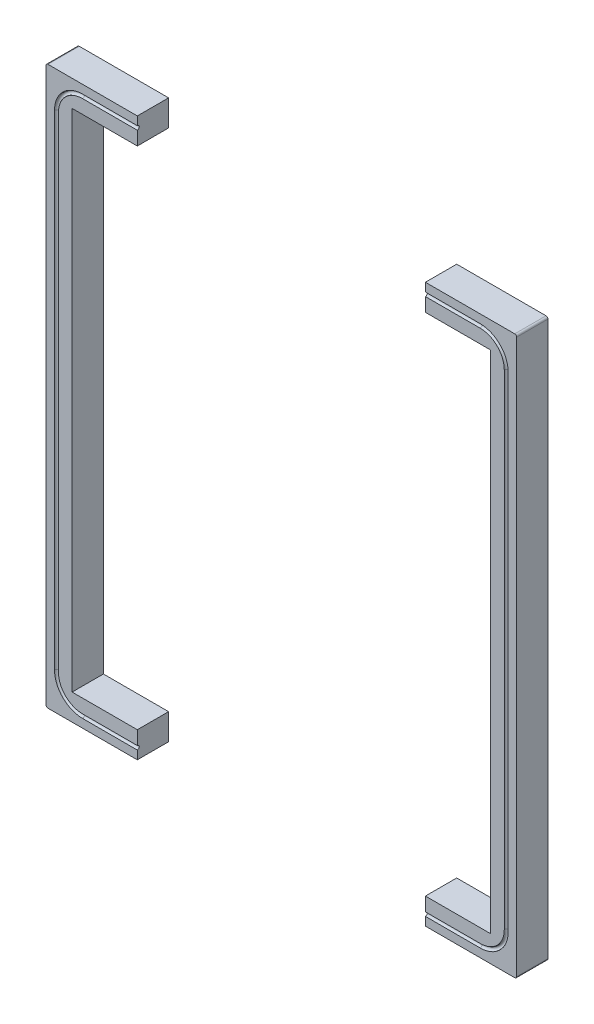
SolidWorks part; units mm, degrees
material "Melamine resin"
ref_plane "Plano frontal" through (0, 0, 0) normal (0, 0, 1) x (1, 0, 0)
ref_plane "Plano superior" through (0, 0, 0) normal (0, 1, 0) x (1, 0, 0)
ref_plane "Plano direito" through (0, 0, 0) normal (1, 0, 0) x (0, 0, -1)
sketch "Esboço1" plane through (0, 0, 0) normal (0, 0, 1) x (1, 0, 0)
  line L1 (-76.152, 222.0831) -> (104.318, 222.0831)
  line L2 (-76.152, 222.0831) -> (-76.152, 8.2431)
  line L3 (-76.152, 8.2431) -> (104.318, 8.2431)
  line L4 (104.318, 222.0831) -> (104.318, 8.2431)
  dimension "D1" = 180.47
  dimension "D2" = 213.84
extrude "Ressalto-extrusão1" add sketch "Esboço1" along normal blind 12
fillet "Filete2" radius 0.7366 1 edges at (104.318, 222.0831, 6)
fillet "Filete3" radius 0.7366 1 edges at (104.318, 8.2431, 6)
fillet "Filete4" radius 0.7366 1 edges at (-76.152, 8.2431, 6)
fillet "Filete5" radius 0.7366 1 edges at (-76.152, 222.0831, 6)
sketch "Esboço2" plane through (0, 0, 12) normal (0, 0, 1) x (1, 0, 0)
  line L0 (69.318, 222.0831) -> (103.5846, 222.0831) construction
  line L1 (-66.152, 212.0831) -> (94.318, 212.0831)
  line L2 (-66.152, 212.0831) -> (-66.152, 18.2431)
  line L3 (-66.152, 18.2431) -> (94.318, 18.2431)
  line L4 (94.318, 212.0831) -> (94.318, 18.2431)
  line L5 (104.318, 8.9797) -> (104.318, 221.3465) construction
  line L6 (-75.4154, 8.2431) -> (103.5814, 8.2431) construction
  line L7 (-76.152, 221.3465) -> (-76.152, 8.9797) construction
  dimension "D1" = 10
  dimension "D2" = 10
  dimension "D3" = 10
  dimension "D4" = 10
extrude "Corte-extrusão1" cut sketch "Esboço2" against normal up to next
sketch "Esboço3" plane through (0, 0, 12) normal (0, 0, 1) x (1, 0, 0)
  line L0 (103.5814, 222.0831) -> (-75.4154, 222.0831) construction
  line L1 (-62.152, 218.0831) -> (90.318, 218.0831)
  line L2 (-72.152, 208.0831) -> (-72.152, 22.2431)
  line L3 (-62.152, 12.2431) -> (90.318, 12.2431)
  line L4 (100.318, 208.0831) -> (100.318, 22.2431)
  line L5 (104.318, 8.9797) -> (104.318, 221.3465) construction
  line L6 (-75.4154, 8.2431) -> (103.5814, 8.2431) construction
  line L7 (-76.152, 221.3465) -> (-76.152, 8.9797) construction
  arc A0 (-72.152, 22.2431) -> (-62.152, 12.2431) centre (-62.152, 22.2431) ccw
  arc A1 (90.318, 12.2431) -> (100.318, 22.2431) centre (90.318, 22.2431) ccw
  arc A2 (100.318, 208.0831) -> (90.318, 218.0831) centre (90.318, 208.0831) ccw
  arc A3 (-62.152, 218.0831) -> (-72.152, 208.0831) centre (-62.152, 208.0831) ccw
  dimension "D5" = 10
  dimension "D1" = 4
  dimension "D2" = 4
  dimension "D3" = 4
  dimension "D4" = 4
sketch "Esboço4" plane through (0, 0, 0) normal (1, 0, 0) x (0, 0, -1)
  line L0 (-12, 218.0831) -> (-12, 208.0831) construction
  line L1 (-12, 218.0831) -> (-12, 208.0831) construction
  circle A0 centre (-12, 218.0831) radius 0.75
  dimension "D1" = 1.5
sweep "Varredura de corte1" cut profiles "Esboço4" path "Esboço3"
sketch "Esboço5" plane through (0, 222.0831, 0) normal (0, 1, 0) x (-1, 0, 0)
  line L0 (-103.5814, 0) -> (75.4154, 0) construction
  line L1 (-69.318, 0) -> (41.152, 0)
  line L2 (-69.318, 0) -> (-69.318, 12)
  line L3 (-69.318, 12) -> (41.152, 12)
  line L4 (41.152, 0) -> (41.152, 12)
  line L5 (-103.5814, 12) -> (75.4154, 12) construction
  line L6 (76.152, 12) -> (76.152, 0) construction
  line L7 (-104.318, 0) -> (-104.318, 12) construction
  dimension "D1" = 35
  dimension "D2" = 35
extrude "Corte-extrusão2" cut sketch "Esboço5" against normal up to next
sketch "Esboço6" plane through (0, 8.2431, 0) normal (0, -1, 0) x (1, 0, 0)
  line L0 (-75.4154, 12) -> (103.5814, 12) construction
  line L1 (69.318, 12) -> (-41.152, 12)
  line L2 (69.318, 12) -> (69.318, 0)
  line L3 (69.318, 0) -> (-41.152, 0)
  line L4 (-41.152, 12) -> (-41.152, 0)
  line L5 (-75.4154, 0) -> (103.5814, 0) construction
  line L6 (-76.152, 0) -> (-76.152, 12) construction
  line L7 (104.318, 12) -> (104.318, 0) construction
  dimension "D1" = 35
  dimension "D2" = 35
extrude "Corte-extrusão3" cut sketch "Esboço6" against normal up to next
